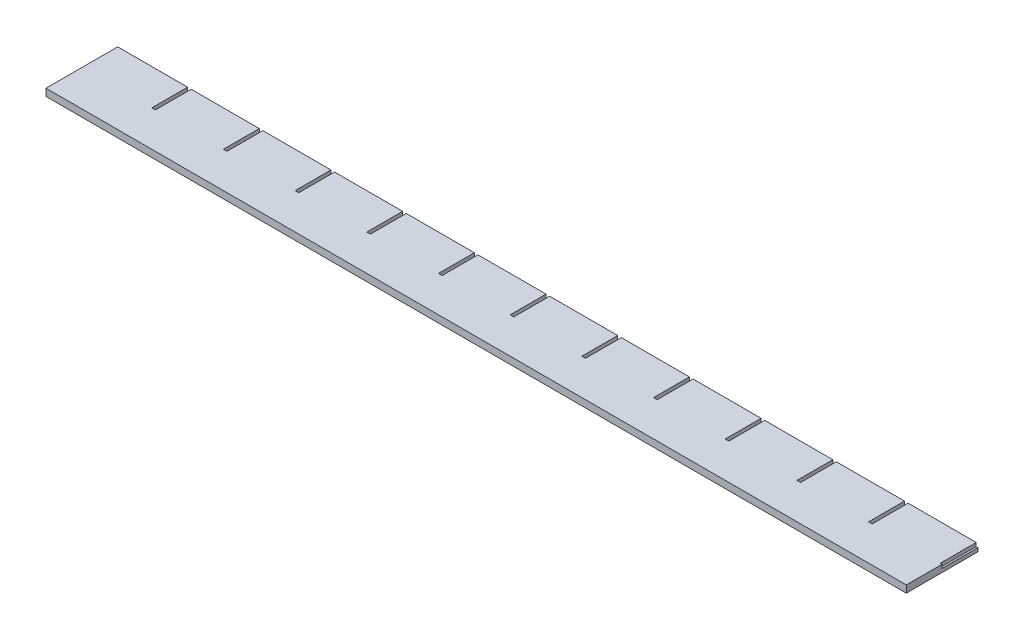
SolidWorks part; units mm, degrees
ref_plane "Front Plane" through (0, 0, 0) normal (0, 0, 1) x (1, 0, 0)
ref_plane "Top Plane" through (0, 0, 0) normal (0, 1, 0) x (1, 0, 0)
ref_plane "Right Plane" through (0, 0, 0) normal (1, 0, 0) x (0, 0, -1)
sketch "Sketch1" plane through (0, 0, 0) normal (0, 1, 0) x (1, 0, 0)
  line L1 (-152.4, 12.7) -> (152.4, 12.7)
  line L2 (-152.4, 12.7) -> (-152.4, -12.7)
  line L3 (-152.4, -12.7) -> (152.4, -12.7)
  line L4 (152.4, 12.7) -> (152.4, -12.7)
  line L5 (-152.4, 12.7) -> (152.4, -12.7) construction
  line L6 (-152.4, -12.7) -> (152.4, 12.7) construction
  point P0 (0, 0)
  dimension "D1" = 304.8
  dimension "D2" = 25.4
extrude "Boss-Extrude1" add sketch "Sketch1" along normal blind 2.54
sketch "Sketch2" plane through (0, 2.54, 0) normal (0, 1, 0) x (1, 0, 0)
  line L0 (152.4, 12.7) -> (-152.4, 12.7) construction
  line L1 (-127.635, 12.7) -> (-126.365, 12.7)
  line L2 (-127.635, 12.7) -> (-127.635, 0)
  line L3 (-127.635, 0) -> (-126.365, 0)
  line L4 (-126.365, 12.7) -> (-126.365, 0)
  line L5 (-127, 0) -> (-127, 12.7)
  line L6 (-152.4, 12.7) -> (-152.4, -12.7) construction
  line L7 (-102.235, 12.7) -> (-102.235, 0)
  line L8 (-101.6, 0) -> (-101.6, 12.7)
  line L9 (-100.965, 12.7) -> (-100.965, 0)
  line L10 (-102.235, 0) -> (-100.965, 0)
  line L11 (-102.235, 12.7) -> (-100.965, 12.7)
  line L12 (-76.835, 12.7) -> (-76.835, 0)
  line L13 (-76.2, 0) -> (-76.2, 12.7)
  line L14 (-75.565, 12.7) -> (-75.565, 0)
  line L15 (-76.835, 0) -> (-75.565, 0)
  line L16 (-76.835, 12.7) -> (-75.565, 12.7)
  line L17 (-51.435, 12.7) -> (-51.435, 0)
  line L18 (-50.8, 0) -> (-50.8, 12.7)
  line L19 (-50.165, 12.7) -> (-50.165, 0)
  line L20 (-51.435, 0) -> (-50.165, 0)
  line L21 (-51.435, 12.7) -> (-50.165, 12.7)
  line L22 (-26.035, 12.7) -> (-26.035, 0)
  line L23 (-25.4, 0) -> (-25.4, 12.7)
  line L24 (-24.765, 12.7) -> (-24.765, 0)
  line L25 (-26.035, 0) -> (-24.765, 0)
  line L26 (-26.035, 12.7) -> (-24.765, 12.7)
  line L27 (-0.635, 12.7) -> (-0.635, 0)
  line L28 (0, 0) -> (0, 12.7)
  line L29 (0.635, 12.7) -> (0.635, 0)
  line L30 (-0.635, 0) -> (0.635, 0)
  line L31 (-0.635, 12.7) -> (0.635, 12.7)
  line L32 (24.765, 12.7) -> (24.765, 0)
  line L33 (25.4, 0) -> (25.4, 12.7)
  line L34 (26.035, 12.7) -> (26.035, 0)
  line L35 (24.765, 0) -> (26.035, 0)
  line L36 (24.765, 12.7) -> (26.035, 12.7)
  line L37 (50.165, 12.7) -> (50.165, 0)
  line L38 (50.8, 0) -> (50.8, 12.7)
  line L39 (51.435, 12.7) -> (51.435, 0)
  line L40 (50.165, 0) -> (51.435, 0)
  line L41 (50.165, 12.7) -> (51.435, 12.7)
  line L42 (75.565, 12.7) -> (75.565, 0)
  line L43 (76.2, 0) -> (76.2, 12.7)
  line L44 (76.835, 12.7) -> (76.835, 0)
  line L45 (75.565, 0) -> (76.835, 0)
  line L46 (75.565, 12.7) -> (76.835, 12.7)
  line L47 (100.965, 12.7) -> (100.965, 0)
  line L48 (101.6, 0) -> (101.6, 12.7)
  line L49 (102.235, 12.7) -> (102.235, 0)
  line L50 (100.965, 0) -> (102.235, 0)
  line L51 (100.965, 12.7) -> (102.235, 12.7)
  line L52 (126.365, 12.7) -> (126.365, 0)
  line L53 (127, 0) -> (127, 12.7)
  line L54 (127.635, 12.7) -> (127.635, 0)
  line L55 (126.365, 0) -> (127.635, 0)
  line L56 (126.365, 12.7) -> (127.635, 12.7)
  line L57 (151.765, 12.7) -> (151.765, 0)
  line L58 (152.4, 0) -> (152.4, 12.7)
  line L59 (153.035, 12.7) -> (153.035, 0)
  line L60 (151.765, 0) -> (153.035, 0)
  line L61 (151.765, 12.7) -> (153.035, 12.7)
  line M61 (152.4, -12.7) -> (152.4, 12.7)
  line M62 (152.4, 12.7) -> (-152.4, 12.7)
  dimension "D1" = 1.27
  dimension "D2" = 12.7
  dimension "D3" = 25.4
  dimension "D5" = 25.4
  dimension "D4" = 12
extrude "Cut-Extrude1" cut sketch "Sketch2" against normal blind 1.27 contours L3 L5 L1 L2 | L5 L3 L4 M62 | L7 L10 L8 M62 | L8 L10 L9 M62 | L13 L15 L14 M62 | L12 L15 L13 M62 | L17 L20 L18 M62 | L18 L20 L19 M62 | L22 L25 L23 M62 | L23 L25 L24 M62 | L27 L30 L28 M62 | L28 L30 L29 M62 | L32 L35 L33 M62 | L33 L35 L34 M62 | L37 L40 L38 M62 | L38 L40 L39 M62 | L42 L45 L43 M62 | L43 L45 L44 M62 | L47 L50 L48 M62 | L48 L50 L49 M62 | L52 L55 L53 M62 | L53 L55 L54 M62 | L57 L60 M61 M62
